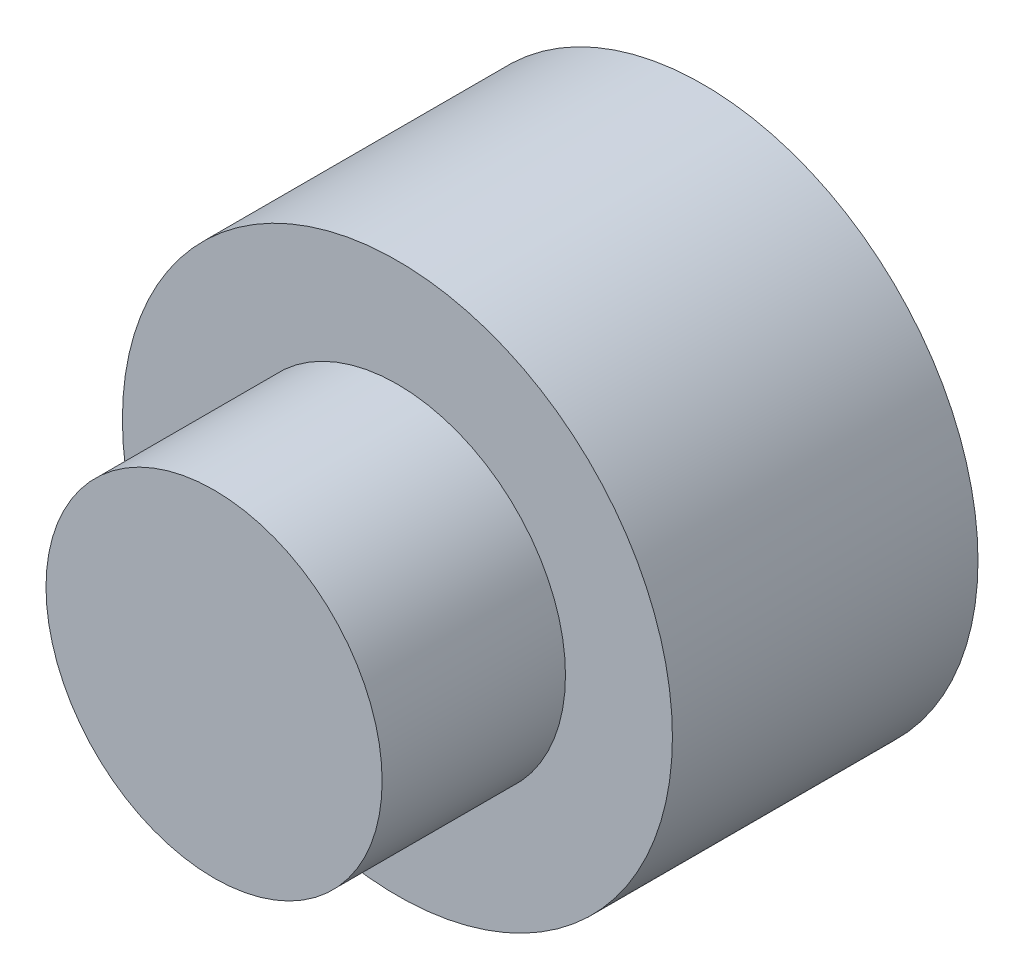
SolidWorks part; units mm, degrees
ref_plane "Front Plane" through (0, 0, 0) normal (0, 0, 1) x (1, 0, 0)
ref_plane "Top Plane" through (0, 0, 0) normal (0, 1, 0) x (1, 0, 0)
ref_plane "Right Plane" through (0, 0, 0) normal (1, 0, 0) x (0, 0, -1)
sketch "Sketch1" plane through (0, 0, 0) normal (0, 1, 0) x (1, 0, 0)
  line L0 (0, 18.0172) -> (0, -14.319) construction
  line L1 (-4.5, 0.319) -> (-4.5, -4.681)
  line L2 (-4.5, -4.681) -> (-2.75, -4.681)
  line L3 (-2.75, -4.681) -> (-2.75, -7.681)
  line L4 (-2.75, -7.681) -> (0, -7.681)
  line L5 (-4.5, 0.319) -> (0, 0.319)
  line L6 (0, 0.319) -> (0, -7.681)
  dimension "D1" = 5.5
  dimension "D2" = 5.5
  dimension "D3" = 3
  dimension "D4" = 9
  dimension "D5" = 5
revolve "Revolve1" add sketch "Sketch1" angle 360 about L0
